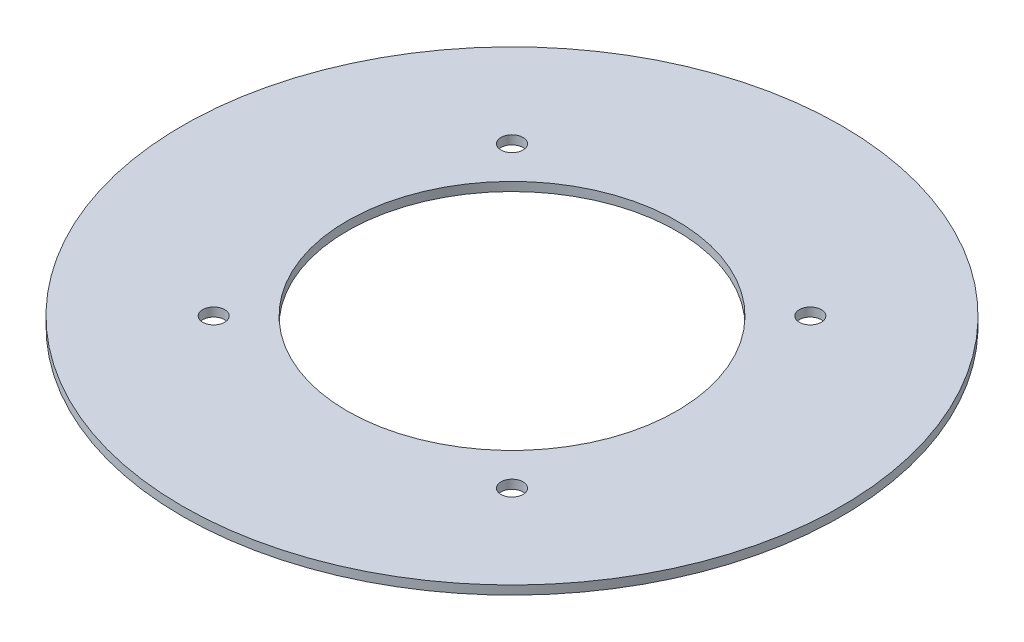
SolidWorks part; units mm, degrees
ref_plane "Front Plane" through (0, 0, 0) normal (0, 0, 1) x (1, 0, 0)
ref_plane "Top Plane" through (0, 0, 0) normal (0, 1, 0) x (1, 0, 0)
ref_plane "Right Plane" through (0, 0, 0) normal (1, 0, 0) x (0, 0, -1)
sketch "Sketch1" plane through (0, 0, 0) normal (0, 1, 0) x (1, 0, 0)
  circle A0 centre (0, 0) radius 75
  circle A1 centre (0, 0) radius 37.5
  dimension "D1" = 150
  dimension "D2" = 75
extrude "Boss-Extrude1" add sketch "Sketch1" along normal blind 2
sketch "Sketch2" plane through (0, 2, 0) normal (0, 1, 0) x (1, 0, 0)
  line L8 (0, 0) -> (0, 17.9951) construction
  line L9 (0, 0) -> (-15.1521, 0) construction
  line L10 (0, 0) -> (-13.9805, 13.9805) construction
  line L11 (0, 0) -> (-13.4873, -13.4873) construction
  circle A8 centre (-33.9411, 33.9411) radius 2.5
  circle A9 centre (33.9411, 33.9411) radius 2.5
  circle A10 centre (33.9411, -33.9411) radius 2.5
  circle A11 centre (-33.9411, -33.9411) radius 2.5
  dimension "D1" = 45
  dimension "D3" = 5
  dimension "D2" = 45
  dimension "D4" = 48
  dimension "D5" = 48
  dimension "D6" = 48
  dimension "D7" = 48
extrude "Cut-Extrude1" cut sketch "Sketch2" against normal blind 10
